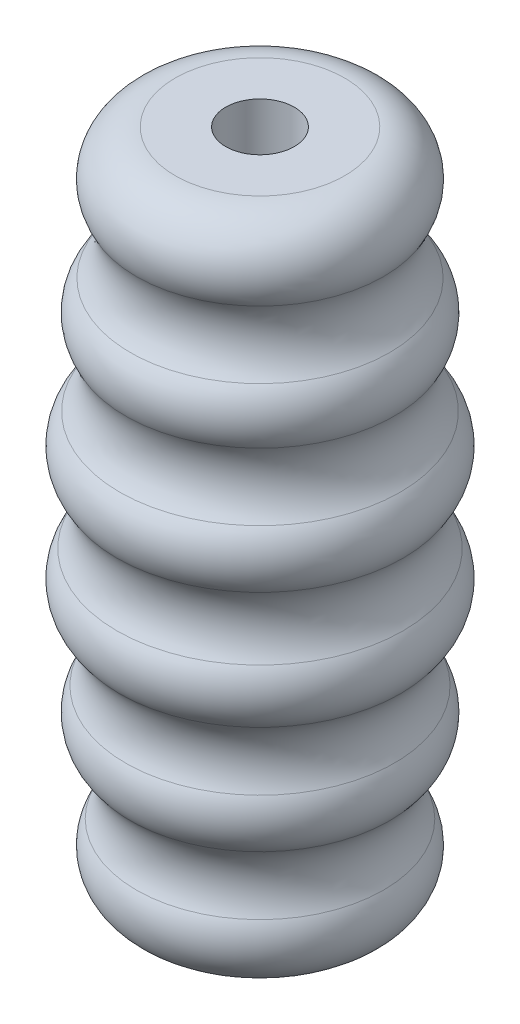
SolidWorks part; units mm, degrees
ref_plane "Ön Düzlem" through (0, 0, 0) normal (0, 0, 1) x (1, 0, 0)
ref_plane "Üst Düzlem" through (0, 0, 0) normal (0, 1, 0) x (1, 0, 0)
ref_plane "Sağ Düzlem" through (0, 0, 0) normal (1, 0, 0) x (0, 0, -1)
sketch "Çizim1" plane through (0, 0, 0) normal (0, 0, 1) x (1, 0, 0)
  line L0 (0, 25.8857) -> (0, -25.8857) construction
  line L1 (-5.9, 3.2) -> (-5.9, -3.2) construction
  line L2 (-5.3, 9.6) -> (-5.3, -9.6) construction
  line L3 (-4.7, 16) -> (-4.7, -16) construction
  line L4 (-8.4, 18.4276) -> (-8.4, -18.4276) construction
  line L5 (-31.8237, 18.5) -> (18.4281, 18.5) construction
  line L6 (-31.8237, -18.5) -> (18.4281, -18.5) construction
  line L7 (-4.7, 18.5) -> (-1.9, 18.5)
  line L8 (-4.7, -18.5) -> (-1.9, -18.5)
  line L9 (-1.9, 18.5) -> (-1.9, -18.5)
  arc A0 (-4.7, 18.5) -> (-6.8562, 14.7348) centre (-4.7, 16) ccw
  arc A1 (-7.1835, 11.2439) -> (-7.4562, 8.3348) centre (-5.3, 9.6) ccw
  arc A2 (-7.9333, -1.7455) -> (-7.7835, -4.8439) centre (-5.9, -3.2) ccw
  arc A3 (-7.4562, -8.3348) -> (-7.1835, -11.2439) centre (-5.3, -9.6) ccw
  arc A4 (-6.8562, -14.7348) -> (-4.7, -18.5) centre (-4.7, -16) ccw
  arc A5 (-7.7835, 4.8439) -> (-7.9333, 1.7455) centre (-5.9, 3.2) ccw
  arc A6 (-7.1835, 11.2439) -> (-6.8562, 14.7348) centre (-9.4437, 13.2166) ccw
  arc A7 (-7.7835, 4.8439) -> (-7.4562, 8.3348) centre (-10.0437, 6.8166) ccw
  arc A8 (-7.9333, -1.7455) -> (-7.9333, 1.7455) centre (-10.3733, 0) ccw
  arc A9 (-7.4562, -8.3348) -> (-7.7835, -4.8439) centre (-10.0437, -6.8166) ccw
  arc A10 (-6.8562, -14.7348) -> (-7.1835, -11.2439) centre (-9.4437, -13.2166) ccw
  point P3 (0, 0)
  point P16 (-5.9, 0)
  point P17 (-5.3, 0)
  point P18 (-4.7, 0)
  point P21 (-8.4, 0)
  dimension "D1" = 5
  dimension "D5" = 6
  dimension "D2" = 8.4
  dimension "D3" = 0.6
  dimension "D4" = 0.6
  dimension "D6" = 37
  dimension "D7" = 6.4
  dimension "D8" = 6.4
  dimension "D9" = 3.8
revolve "Döndür1" add sketch "Çizim1" angle 360 about L0
